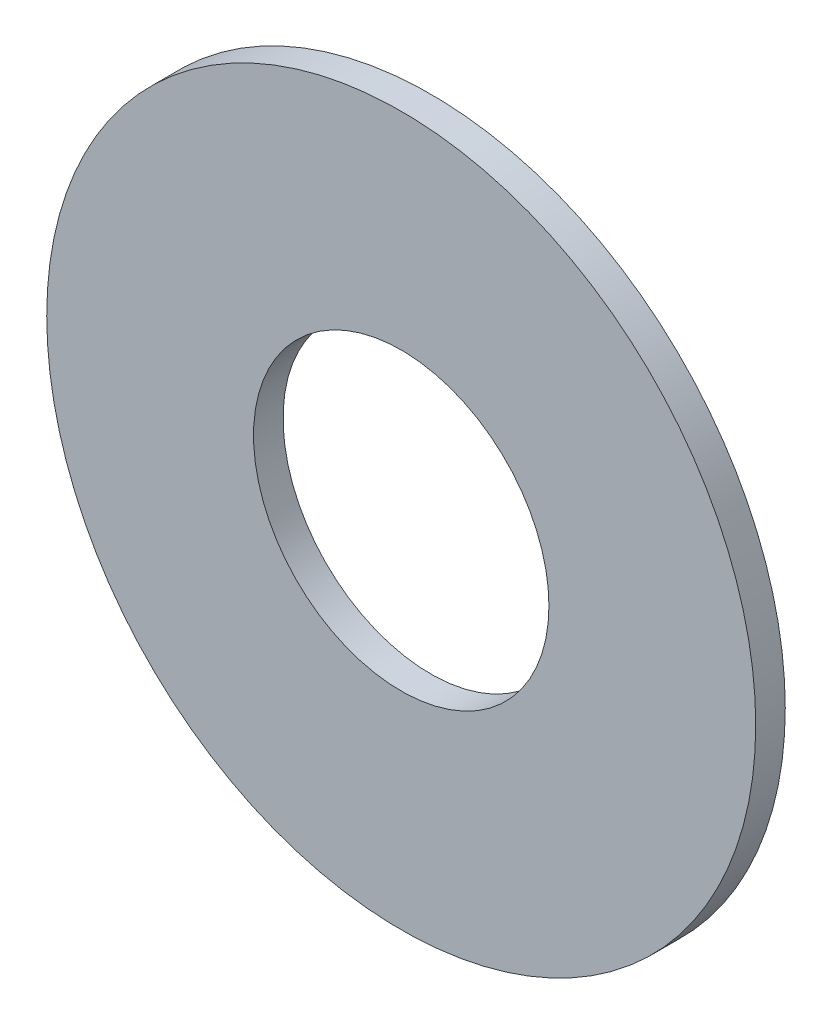
SolidWorks part; units mm, degrees
ref_plane "Plano frontal" through (0, 0, 0) normal (0, 0, 1) x (1, 0, 0)
ref_plane "Plano superior" through (0, 0, 0) normal (0, 1, 0) x (1, 0, 0)
ref_plane "Plano direito" through (0, 0, 0) normal (1, 0, 0) x (0, 0, -1)
sketch "Esboço1" plane through (0, 0, 0) normal (0, 0, 1) x (1, 0, 0)
  circle A0 centre (0, 0) radius 6
  dimension "D1" = 12
extrude "Ressalto-extrusão1" add sketch "Esboço1" along normal blind 0.5
sketch "Esboço2" plane through (0, 0, 0.5) normal (0, 0, 1) x (1, 0, 0)
  circle A0 centre (0, 0) radius 2.5
  dimension "D1" = 5
extrude "Corte-extrusão1" cut sketch "Esboço2" against normal through all
